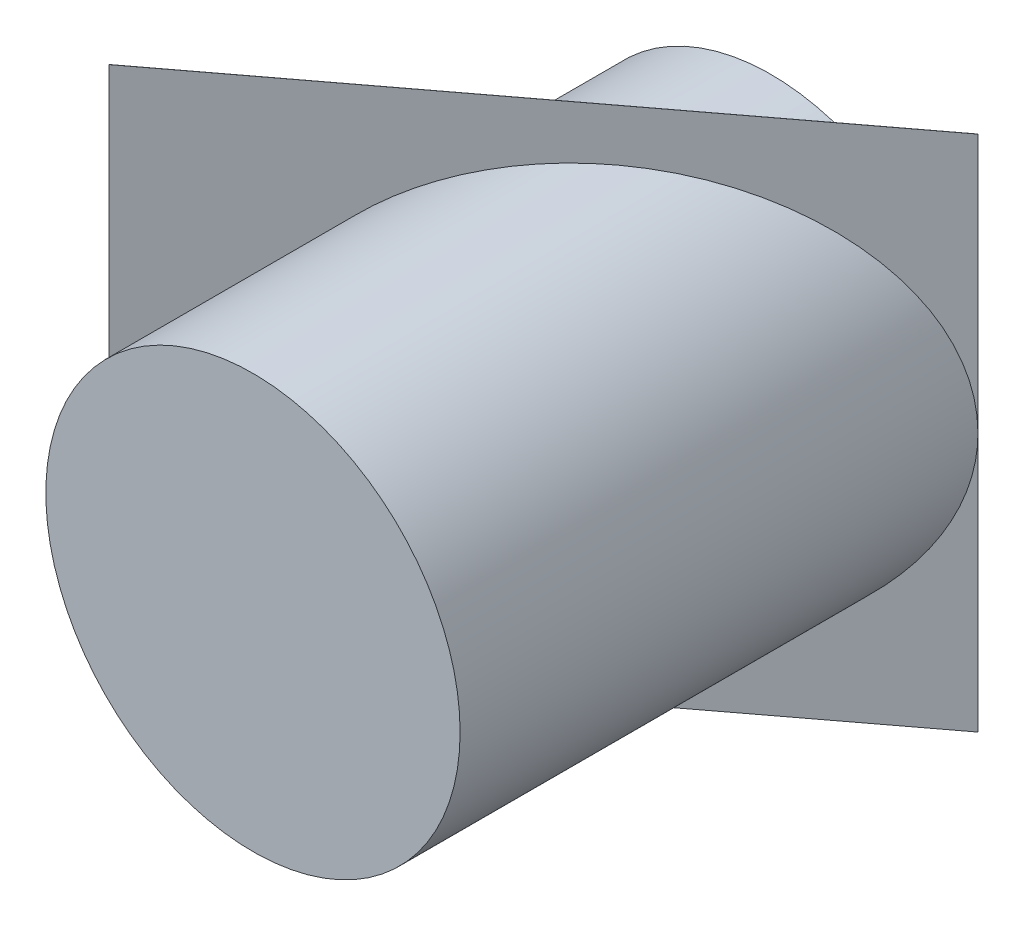
SolidWorks part; units mm, degrees
ref_plane "前视基准面" through (0, 0, 0) normal (0, 0, 1) x (1, 0, 0)
ref_plane "上视基准面" through (0, 0, 0) normal (0, 1, 0) x (1, 0, 0)
ref_plane "右视基准面" through (0, 0, 0) normal (1, 0, 0) x (0, 0, -1)
sketch "草图1" plane through (0, 0, 0) normal (0, 0, 1) x (1, 0, 0)
  circle A0 centre (0, 0) radius 20
extrude "凸台-拉伸1" add sketch "草图1" along normal blind 50
sketch "草图3" plane through (0, 0, 0) normal (0, 1, 0) x (1, 0, 0)
  line L0 (20, 0) -> (-27.7557, -36.1284)
  point P3 (-27.7557, -36.1284)
  point P5 (-20, -30.4469)
extrude "拉伸-薄壁1" add sketch "草图3" along normal mid plane 50 thin
sketch "草图6" plane through (0, 0, 0) normal (0, 0, 1) x (1, 0, 0)
  line L0 (-20, 0) -> (20, 0) construction
  circle A0 centre (0, 0) radius 20 construction
sketch "草图7" plane through (0, 0, 0) normal (0, 1, 0) x (1, 0, 0)
  line L0 (-20, -30.261) -> (20, 0) construction
